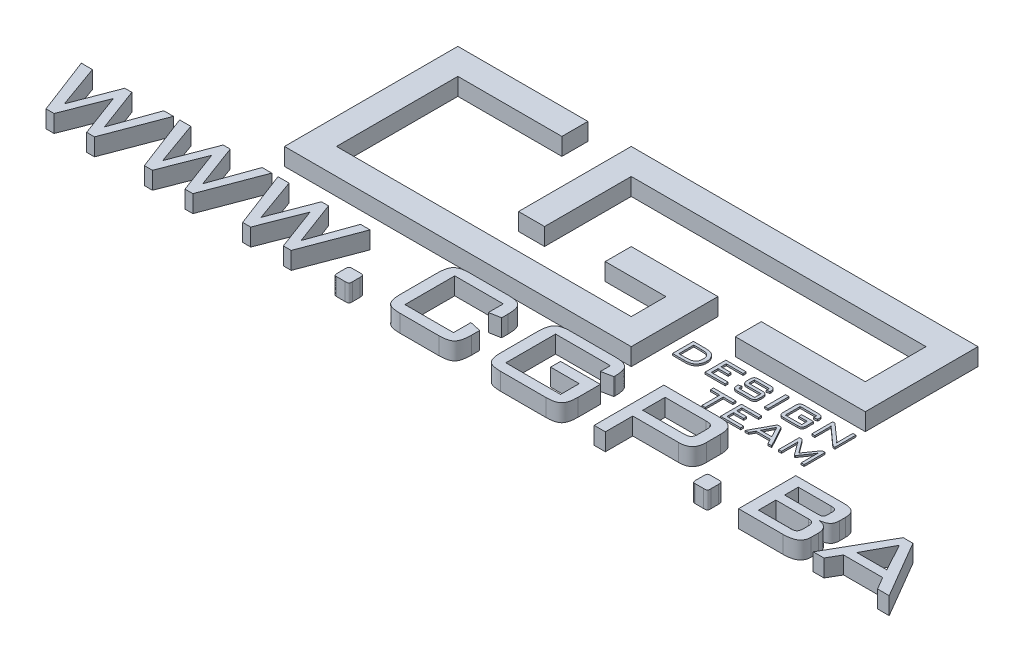
SolidWorks part; units mm, degrees
ref_plane "Front Plane" through (0, 0, 0) normal (0, 0, 1) x (1, 0, 0)
ref_plane "Top Plane" through (0, 0, 0) normal (0, 1, 0) x (1, 0, 0)
ref_plane "Right Plane" through (0, 0, 0) normal (1, 0, 0) x (0, 0, -1)
sketch "Sketch1" plane through (0, 0, 0) normal (0, 0, 1) x (1, 0, 0)
  line L0 (-150, 0) -> (50, 0)
  line L1 (50, 0) -> (50, 50)
  line L2 (50, 50) -> (0, 50)
  line L3 (-150, 0) -> (-150, 100)
  line L4 (-150, 100) -> (-75, 100)
  line L5 (-50, 100) -> (150, 100)
  line L6 (150, 100) -> (150, 35)
  line L7 (150, 35) -> (75, 35)
  line L8 (35, 35) -> (0, 35)
  line L9 (35, 15) -> (35, 35)
  line L10 (-135, 15) -> (35, 15)
  line L11 (-135, 15) -> (-135, 85)
  line L12 (-135, 85) -> (-75, 85)
  line L13 (-50, 100) -> (-50, 35)
  line L14 (135, 50) -> (75, 50)
  line L15 (135, 85) -> (135, 50)
  line L16 (-35, 85) -> (135, 85)
  line L17 (-35, 85) -> (-35, 35)
  line L18 (-35, 35) -> (-50, 35)
  line L19 (-75, 100) -> (-75, 85)
  line L20 (0, 50) -> (0, 35)
  line L21 (75, 50) -> (75, 35)
  dimension "D1" = 200
  dimension "D2" = 50
  dimension "D3" = 50
  dimension "D4" = 100
  dimension "D5" = 75
  dimension "D6" = 200
  dimension "D8" = 25
  dimension "D9" = 75
  dimension "D10" = 15
  dimension "D11" = 15
sketch "Sketch4" plane through (0, 0, 0) normal (0, 1, 0) x (1, 0, 0)
  line L0 (-150, -35) -> (50, -35)
  line L1 (50, -35) -> (50, 15)
  line L2 (50, 15) -> (0, 15)
  line L3 (-150, -35) -> (-150, 65)
  line L4 (-150, 65) -> (-75, 65)
  line L5 (-50, 65) -> (150, 65)
  line L6 (150, 65) -> (150, 0)
  line L7 (150, 0) -> (75, 0)
  line L8 (35, 0) -> (0, 0)
  line L9 (35, -20) -> (35, 0)
  line L10 (-135, -20) -> (35, -20)
  line L11 (-135, -20) -> (-135, 50)
  line L12 (-135, 50) -> (-75, 50)
  line L13 (-50, 65) -> (-50, 0)
  line L14 (135, 15) -> (75, 15)
  line L15 (135, 50) -> (135, 15)
  line L16 (-35, 50) -> (135, 50)
  line L17 (-35, 50) -> (-35, 0)
  line L18 (-35, 0) -> (-50, 0)
  line L19 (-75, 65) -> (-75, 50)
  line L20 (0, 15) -> (0, 0)
  line L21 (75, 15) -> (75, 0)
  dimension "D1" = 200
  dimension "D2" = 50
  dimension "D3" = 50
  dimension "D4" = 100
  dimension "D5" = 75
  dimension "D6" = 200
  dimension "D7" = 25
  dimension "D8" = 75
  dimension "D9" = 15
  dimension "D10" = 50
  dimension "D11" = 70
  dimension "D12" = 60
  dimension "D13" = 170
  dimension "D14" = 35
  dimension "D15" = 20
  dimension "D16" = 170
  dimension "D17" = 15
extrude "Boss-Extrude2" add sketch "Sketch4" along normal blind 10
sketch "Sketch6" plane through (0, 0, 0) normal (0, 1, 0) x (1, 0, 0)
  line L0 (50, -17.5) -> (153, -17.5) construction
  line L1 (-150, -35) -> (50, -35) construction
  line L2 (50, -35) -> (153, -35) construction
  line L3 (50, -35) -> (50, 15) construction
  text T0 "DESIGN" font "BankGothic Lt BT" height in points 45
  text T1 "TEAM" font "BankGothic Lt BT" height in points 45
  dimension "D1" = 103
  dimension "D2" = 103
  dimension "D3" = 17.5
extrude "Boss-Extrude4" add sketch "Sketch6" along normal blind 1 separate body
sketch "Sketch7" plane through (0, 0, 0) normal (0, 1, 0) x (1, 0, 0)
  line L0 (-150, -61.1733) -> (50, -61.1733) construction
  line L1 (-83.6915, -73.2799) -> (8.5878, -73.2799) construction
  line L2 (-83.6915, -82.2799) -> (8.5878, -82.2799) construction
  line L3 (-83.6915, -91.2799) -> (8.5878, -91.2799) construction
  line L4 (-83.6915, -100.2799) -> (8.5878, -100.2799) construction
  line L5 (-83.6915, -109.2799) -> (8.5878, -109.2799) construction
  line L6 (-83.6915, -118.2799) -> (8.5878, -118.2799) construction
  text T0 "Engineering-Design-Architecture-IT \r\nEducation:" font "BankGothic Lt BT" height in points 20
  text T1 "Solidworks\r\n" font "BankGothic Lt BT" height in points 21
  text T2 "AutoCAD" font "BankGothic Lt BT" height in points 21
  text T3 "CATIA V5" font "BankGothic Lt BT" height in points 21
  text T4 "3D Printing" font "BankGothic Lt BT" height in points 21
  text T5 "3ds MAX" font "BankGothic Lt BT" height in points 21
  text T6 "Maya 3D" font "BankGothic Lt BT" height in points 21
  dimension "D1" = 9
  dimension "D2" = 9
  dimension "D3" = 9
  dimension "D4" = 9
  dimension "D5" = 9
extrude "Boss-Extrude5" [suppressed] add sketch "Sketch7" along normal blind 1 separate body
sketch "Sketch9" plane through (0, 0, 0) normal (0, 1, 0) x (1, 0, 0)
  line L0 (-350, -85) -> (350, -85) construction
  line L1 (-150, -35) -> (50, -35) construction
  text T0 "www.CGP.ba" font "BankGothic Lt BT" height in points 150
  dimension "D1" = 700
  dimension "D2" = 350
  dimension "D3" = 50
extrude "Boss-Extrude6" add sketch "Sketch9" along normal up to surface (10 mm away) separate body up to face at (-45.8333, 10, -12.5)
sketch "Sketch8" plane through (0, 0, 0) normal (0, 1, 0) x (1, 0, 0)
  line L0 (-50, 65) -> (-50, 0) construction
  line L1 (-50, 0) -> (-35, 0) construction
  line L2 (-35, 0) -> (-35, 50) construction
  line L3 (-35, 50) -> (135, 50) construction
  line L4 (135, 50) -> (135, 15) construction
  line L5 (135, 15) -> (75, 15) construction
  line L6 (75, 15) -> (75, 0) construction
  line L7 (75, 0) -> (150, 0) construction
  line L8 (150, 0) -> (150, 65) construction
  line L9 (150, 65) -> (-50, 65) construction
  line L10 (-150, 65) -> (-150, -35) construction
  line L11 (-150, -35) -> (50, -35) construction
  line L12 (50, -35) -> (50, 15) construction
  line L13 (50, 15) -> (0, 15) construction
  line L14 (0, 15) -> (0, 0) construction
  line L15 (0, 0) -> (35, 0) construction
  line L16 (35, 0) -> (35, -20) construction
  line L17 (35, -20) -> (-135, -20) construction
  line L18 (-135, -20) -> (-135, 50) construction
  line L19 (-135, 50) -> (-75, 50) construction
  line L20 (-75, 50) -> (-75, 65) construction
  line L21 (-75, 65) -> (-150, 65) construction
  line L22 (-50, 65) -> (-50, 0)
  line L23 (-50, 0) -> (-35, 0)
  line L24 (-35, 0) -> (-35, 50)
  line L25 (-35, 50) -> (135, 50)
  line L26 (135, 50) -> (135, 15)
  line L27 (135, 15) -> (75, 15)
  line L28 (75, 15) -> (75, 0)
  line L29 (75, 0) -> (150, 0)
  line L30 (150, 0) -> (150, 65)
  line L31 (150, 65) -> (-50, 65)
  line L32 (-150, 65) -> (-150, -35)
  line L33 (-150, -35) -> (50, -35)
  line L34 (50, -35) -> (50, 15)
  line L35 (50, 15) -> (0, 15)
  line L36 (0, 15) -> (0, 0)
  line L37 (0, 0) -> (35, 0)
  line L38 (35, 0) -> (35, -20)
  line L39 (35, -20) -> (-135, -20)
  line L40 (-135, -20) -> (-135, 50)
  line L41 (-135, 50) -> (-75, 50)
  line L42 (-75, 50) -> (-75, 65)
  line L43 (-75, 65) -> (-150, 65)
  line L44 (115.7393, -35) -> (117.7046, -35) construction
  line L45 (117.7046, -35) -> (119.2325, -32.2001) construction
  line L46 (119.2325, -32.2001) -> (127.3126, -32.2001) construction
  line L47 (127.3126, -32.2001) -> (128.8371, -35) construction
  line L48 (128.8371, -35) -> (131.0312, -35) construction
  line L49 (131.0312, -35) -> (124.3982, -22.9387) construction
  line L50 (124.3982, -22.9387) -> (122.2612, -22.9387) construction
  line L51 (122.2612, -22.9387) -> (115.7393, -35) construction
  line L52 (137.3614, -26.58) -> (142.2175, -33.1053) construction
  line L53 (142.2175, -33.1053) -> (142.7392, -33.1053) construction
  line L54 (142.7392, -33.1053) -> (147.4102, -26.3949) construction
  line L55 (148.0463, -26.8627) -> (148.0463, -35) construction
  line L56 (148.0463, -35) -> (149.7693, -35) construction
  line L57 (149.7693, -35) -> (149.7693, -22.9387) construction
  line L58 (149.7693, -22.9387) -> (148.0463, -22.9387) construction
  line L59 (148.0463, -22.9387) -> (142.507, -30.79) construction
  line L60 (142.507, -30.79) -> (136.5705, -22.9387) construction
  line L61 (136.5705, -22.9387) -> (134.9081, -22.9387) construction
  line L62 (134.9081, -22.9387) -> (134.9081, -35) construction
  line L63 (134.9081, -35) -> (136.6311, -35) construction
  line L64 (136.6311, -35) -> (136.6311, -26.8627) construction
  line L65 (136.6311, -17.5) -> (138.3542, -17.5) construction
  line L66 (138.3542, -17.5) -> (138.3542, -10.3925) construction
  line L67 (139.4681, -9.1136) -> (148.8405, -17.5) construction
  line L68 (148.8405, -17.5) -> (149.9847, -17.5) construction
  line L69 (149.9847, -17.5) -> (149.9847, -5.4387) construction
  line L70 (149.9847, -5.4387) -> (148.2616, -5.4387) construction
  line L71 (148.2616, -5.4387) -> (148.2616, -12.0583) construction
  line L72 (147.04, -13.5054) -> (137.9133, -5.4387) construction
  line L73 (137.9133, -5.4387) -> (136.6311, -5.4387) construction
  line L74 (136.6311, -5.4387) -> (136.6311, -17.5) construction
  line L75 (92.6936, -24.6618) -> (98.2935, -24.6618) construction
  line L76 (98.2935, -24.6618) -> (98.2935, -22.9387) construction
  line L77 (98.2935, -22.9387) -> (85.3707, -22.9387) construction
  line L78 (85.3707, -22.9387) -> (85.3707, -24.6618) construction
  line L79 (85.3707, -24.6618) -> (90.7552, -24.6618) construction
  line L80 (90.7552, -24.6618) -> (90.7552, -35) construction
  line L81 (90.7552, -35) -> (92.6936, -35) construction
  line L82 (92.6936, -35) -> (92.6936, -24.6618) construction
  line L83 (101.5242, -35) -> (113.1547, -35) construction
  line L84 (113.1547, -35) -> (113.1547, -33.277) construction
  line L85 (113.1547, -33.277) -> (103.4626, -33.277) construction
  line L86 (103.4626, -33.277) -> (103.4626, -29.4001) construction
  line L87 (103.4626, -29.4001) -> (109.2779, -29.4001) construction
  line L88 (109.2779, -29.4001) -> (109.2779, -27.6771) construction
  line L89 (109.2779, -27.6771) -> (103.4626, -27.6771) construction
  line L90 (103.4626, -27.6771) -> (103.4626, -24.6618) construction
  line L91 (103.4626, -24.6618) -> (113.1547, -24.6618) construction
  line L92 (113.1547, -24.6618) -> (113.1547, -22.9387) construction
  line L93 (113.1547, -22.9387) -> (101.5242, -22.9387) construction
  line L94 (101.5242, -22.9387) -> (101.5242, -35) construction
  line L95 (129.0928, -7.1618) -> (129.0928, -8.8848) construction
  line L96 (129.0928, -8.8848) -> (131.0312, -8.4944) construction
  line L97 (131.0312, -8.4944) -> (131.0312, -8.205) construction
  line L98 (128.2582, -5.4387) -> (120.4305, -5.4387) construction
  line L99 (117.6777, -8.3396) -> (117.6777, -14.7034) construction
  line L100 (120.4305, -17.5) -> (128.2582, -17.5) construction
  line L101 (131.0312, -14.7034) -> (131.0312, -10.8232) construction
  line L102 (131.0312, -10.8232) -> (124.1391, -10.8232) construction
  line L103 (124.1391, -10.8232) -> (124.1391, -12.5463) construction
  line L104 (124.1391, -12.5463) -> (129.0928, -12.5463) construction
  line L105 (129.0928, -12.5463) -> (129.0928, -15.777) construction
  line L106 (129.0928, -15.777) -> (119.6161, -15.777) construction
  line L107 (119.6161, -15.777) -> (119.6161, -7.1618) construction
  line L108 (119.6161, -7.1618) -> (129.0928, -7.1618) construction
  line L109 (109.4932, -17.5) -> (111.4317, -17.5) construction
  line L110 (111.4317, -17.5) -> (111.4317, -5.4387) construction
  line L111 (111.4317, -5.4387) -> (109.4932, -5.4387) construction
  line L112 (109.4932, -5.4387) -> (109.4932, -17.5) construction
  line L113 (101.7396, -7.1618) -> (101.7396, -8.8848) construction
  line L114 (101.7396, -8.8848) -> (103.4626, -8.4002) construction
  line L115 (103.4626, -8.4002) -> (103.4626, -8.1512) construction
  line L116 (100.6223, -5.4387) -> (94.1373, -5.4387) construction
  line L117 (91.4013, -8.3564) -> (91.4013, -9.3627) construction
  line L118 (94.1373, -12.1155) -> (101.9549, -12.1155) construction
  line L119 (101.9549, -12.1155) -> (101.9549, -15.777) construction
  line L120 (101.9549, -15.777) -> (92.6936, -15.777) construction
  line L121 (92.6936, -15.777) -> (92.6936, -13.8385) construction
  line L122 (92.6936, -13.8385) -> (90.9706, -14.2727) construction
  line L123 (90.9706, -14.2727) -> (90.9706, -14.6025) construction
  line L124 (93.6897, -17.5) -> (100.7939, -17.5) construction
  line L125 (103.678, -14.6025) -> (103.678, -13.2328) construction
  line L126 (100.7939, -10.3925) -> (93.1244, -10.3925) construction
  line L127 (93.1244, -10.3925) -> (93.1244, -7.1618) construction
  line L128 (93.1244, -7.1618) -> (101.7396, -7.1618) construction
  line L129 (75.0324, -17.5) -> (86.663, -17.5) construction
  line L130 (86.663, -17.5) -> (86.663, -15.777) construction
  line L131 (86.663, -15.777) -> (76.9709, -15.777) construction
  line L132 (76.9709, -15.777) -> (76.9709, -11.9001) construction
  line L133 (76.9709, -11.9001) -> (82.7861, -11.9001) construction
  line L134 (82.7861, -11.9001) -> (82.7861, -10.1771) construction
  line L135 (82.7861, -10.1771) -> (76.9709, -10.1771) construction
  line L136 (76.9709, -10.1771) -> (76.9709, -7.1618) construction
  line L137 (76.9709, -7.1618) -> (86.663, -7.1618) construction
  line L138 (86.663, -7.1618) -> (86.663, -5.4387) construction
  line L139 (86.663, -5.4387) -> (75.0324, -5.4387) construction
  line L140 (75.0324, -5.4387) -> (75.0324, -17.5) construction
  line L141 (62.8567, -5.4387) -> (56.2944, -5.4387) construction
  line L142 (56.2944, -5.4387) -> (56.2944, -17.5) construction
  line L143 (56.2944, -17.5) -> (62.8567, -17.5) construction
  line L144 (115.7393, -35) -> (117.7046, -35)
  line L145 (117.7046, -35) -> (119.2325, -32.2001)
  line L146 (119.2325, -32.2001) -> (127.3126, -32.2001)
  line L147 (127.3126, -32.2001) -> (128.8371, -35)
  line L148 (128.8371, -35) -> (131.0312, -35)
  line L149 (131.0312, -35) -> (124.3982, -22.9387)
  line L150 (124.3982, -22.9387) -> (122.2612, -22.9387)
  line L151 (122.2612, -22.9387) -> (115.7393, -35)
  line L152 (137.3614, -26.58) -> (142.2175, -33.1053)
  line L153 (142.2175, -33.1053) -> (142.7392, -33.1053)
  line L154 (142.7392, -33.1053) -> (147.4102, -26.3949)
  line L155 (148.0463, -26.8627) -> (148.0463, -35)
  line L156 (148.0463, -35) -> (149.7693, -35)
  line L157 (149.7693, -35) -> (149.7693, -22.9387)
  line L158 (149.7693, -22.9387) -> (148.0463, -22.9387)
  line L159 (148.0463, -22.9387) -> (142.507, -30.79)
  line L160 (142.507, -30.79) -> (136.5705, -22.9387)
  line L161 (136.5705, -22.9387) -> (134.9081, -22.9387)
  line L162 (134.9081, -22.9387) -> (134.9081, -35)
  line L163 (134.9081, -35) -> (136.6311, -35)
  line L164 (136.6311, -35) -> (136.6311, -26.8627)
  line L165 (136.6311, -17.5) -> (138.3542, -17.5)
  line L166 (138.3542, -17.5) -> (138.3542, -10.3925)
  line L167 (139.4681, -9.1136) -> (148.8405, -17.5)
  line L168 (148.8405, -17.5) -> (149.9847, -17.5)
  line L169 (149.9847, -17.5) -> (149.9847, -5.4387)
  line L170 (149.9847, -5.4387) -> (148.2616, -5.4387)
  line L171 (148.2616, -5.4387) -> (148.2616, -12.0583)
  line L172 (147.04, -13.5054) -> (137.9133, -5.4387)
  line L173 (137.9133, -5.4387) -> (136.6311, -5.4387)
  line L174 (136.6311, -5.4387) -> (136.6311, -17.5)
  line L175 (92.6936, -24.6618) -> (98.2935, -24.6618)
  line L176 (98.2935, -24.6618) -> (98.2935, -22.9387)
  line L177 (98.2935, -22.9387) -> (85.3707, -22.9387)
  line L178 (85.3707, -22.9387) -> (85.3707, -24.6618)
  line L179 (85.3707, -24.6618) -> (90.7552, -24.6618)
  line L180 (90.7552, -24.6618) -> (90.7552, -35)
  line L181 (90.7552, -35) -> (92.6936, -35)
  line L182 (92.6936, -35) -> (92.6936, -24.6618)
  line L183 (101.5242, -35) -> (113.1547, -35)
  line L184 (113.1547, -35) -> (113.1547, -33.277)
  line L185 (113.1547, -33.277) -> (103.4626, -33.277)
  line L186 (103.4626, -33.277) -> (103.4626, -29.4001)
  line L187 (103.4626, -29.4001) -> (109.2779, -29.4001)
  line L188 (109.2779, -29.4001) -> (109.2779, -27.6771)
  line L189 (109.2779, -27.6771) -> (103.4626, -27.6771)
  line L190 (103.4626, -27.6771) -> (103.4626, -24.6618)
  line L191 (103.4626, -24.6618) -> (113.1547, -24.6618)
  line L192 (113.1547, -24.6618) -> (113.1547, -22.9387)
  line L193 (113.1547, -22.9387) -> (101.5242, -22.9387)
  line L194 (101.5242, -22.9387) -> (101.5242, -35)
  line L195 (129.0928, -7.1618) -> (129.0928, -8.8848)
  line L196 (129.0928, -8.8848) -> (131.0312, -8.4944)
  line L197 (131.0312, -8.4944) -> (131.0312, -8.205)
  line L198 (128.2582, -5.4387) -> (120.4305, -5.4387)
  line L199 (117.6777, -8.3396) -> (117.6777, -14.7034)
  line L200 (120.4305, -17.5) -> (128.2582, -17.5)
  line L201 (131.0312, -14.7034) -> (131.0312, -10.8232)
  line L202 (131.0312, -10.8232) -> (124.1391, -10.8232)
  line L203 (124.1391, -10.8232) -> (124.1391, -12.5463)
  line L204 (124.1391, -12.5463) -> (129.0928, -12.5463)
  line L205 (129.0928, -12.5463) -> (129.0928, -15.777)
  line L206 (129.0928, -15.777) -> (119.6161, -15.777)
  line L207 (119.6161, -15.777) -> (119.6161, -7.1618)
  line L208 (119.6161, -7.1618) -> (129.0928, -7.1618)
  line L209 (109.4932, -17.5) -> (111.4317, -17.5)
  line L210 (111.4317, -17.5) -> (111.4317, -5.4387)
  line L211 (111.4317, -5.4387) -> (109.4932, -5.4387)
  line L212 (109.4932, -5.4387) -> (109.4932, -17.5)
  line L213 (101.7396, -7.1618) -> (101.7396, -8.8848)
  line L214 (101.7396, -8.8848) -> (103.4626, -8.4002)
  line L215 (103.4626, -8.4002) -> (103.4626, -8.1512)
  line L216 (100.6223, -5.4387) -> (94.1373, -5.4387)
  line L217 (91.4013, -8.3564) -> (91.4013, -9.3627)
  line L218 (94.1373, -12.1155) -> (101.9549, -12.1155)
  line L219 (101.9549, -12.1155) -> (101.9549, -15.777)
  line L220 (101.9549, -15.777) -> (92.6936, -15.777)
  line L221 (92.6936, -15.777) -> (92.6936, -13.8385)
  line L222 (92.6936, -13.8385) -> (90.9706, -14.2727)
  line L223 (90.9706, -14.2727) -> (90.9706, -14.6025)
  line L224 (93.6897, -17.5) -> (100.7939, -17.5)
  line L225 (103.678, -14.6025) -> (103.678, -13.2328)
  line L226 (100.7939, -10.3925) -> (93.1244, -10.3925)
  line L227 (93.1244, -10.3925) -> (93.1244, -7.1618)
  line L228 (93.1244, -7.1618) -> (101.7396, -7.1618)
  line L229 (75.0324, -17.5) -> (86.663, -17.5)
  line L230 (86.663, -17.5) -> (86.663, -15.777)
  line L231 (86.663, -15.777) -> (76.9709, -15.777)
  line L232 (76.9709, -15.777) -> (76.9709, -11.9001)
  line L233 (76.9709, -11.9001) -> (82.7861, -11.9001)
  line L234 (82.7861, -11.9001) -> (82.7861, -10.1771)
  line L235 (82.7861, -10.1771) -> (76.9709, -10.1771)
  line L236 (76.9709, -10.1771) -> (76.9709, -7.1618)
  line L237 (76.9709, -7.1618) -> (86.663, -7.1618)
  line L238 (86.663, -7.1618) -> (86.663, -5.4387)
  line L239 (86.663, -5.4387) -> (75.0324, -5.4387)
  line L240 (75.0324, -5.4387) -> (75.0324, -17.5)
  line L241 (62.8567, -5.4387) -> (56.2944, -5.4387)
  line L242 (56.2944, -5.4387) -> (56.2944, -17.5)
  line L243 (56.2944, -17.5) -> (62.8567, -17.5)
  line L244 (120.0671, -30.477) -> (126.4982, -30.477) construction
  line L245 (62.5707, -7.1618) -> (58.2328, -7.1618) construction
  line L246 (58.2328, -15.777) -> (62.5707, -15.777) construction
  line L247 (58.2328, -7.1618) -> (58.2328, -15.777) construction
  line L248 (123.2776, -24.3151) -> (120.0671, -30.477) construction
  line L249 (126.4982, -30.477) -> (123.2776, -24.3151) construction
  line L250 (120.0671, -30.477) -> (126.4982, -30.477)
  line L251 (126.4982, -30.477) -> (123.2776, -24.3151)
  line L252 (123.2776, -24.3151) -> (120.0671, -30.477)
  line L253 (58.2328, -7.1618) -> (58.2328, -15.777)
  line L254 (58.2328, -15.777) -> (62.5707, -15.777)
  line L255 (62.5707, -7.1618) -> (58.2328, -7.1618)
  line L256 (-350, -85) -> (350, -85) construction
  spline S0 degree 3 poles (-11857.5173, -5035.0417) (223.8845, 44.5646) (129.8104, -11.8679) (136.8463, -25.7989) (146.9319, -42.5935) (241.0333, -3.6078) (-10668.9913, -7250.1358) knots -28.406317 -28.406317 -28.406317 -28.406317 0.231846 0.47301 0.729943 36.845841 36.845841 36.845841 36.845841 only from (136.5403, -25.0959) to (137.3042, -26.4992) construction
  spline S1 degree 3 poles (-10429.0902, -7596.536) (174.5683, 13.3543) (101.8761, -50.7131) (170.2646, -13.4441) (-10412.5762, -7620.2349) knots -161.421544 -161.421544 -161.421544 -161.421544 0.660055 130.391888 130.391888 130.391888 130.391888 only from (137.3042, -26.4992) to (137.3614, -26.58) construction
  spline S2 degree 3 poles (11167.6876, -6918.2798) (60.9845, -5.6512) (140.7273, -38.4158) (147.7359, -25.8618) (159.6741, -3.8807) (94.5984, 58.2585) (11700.1863, -5984.1183) knots -28.317786 -28.317786 -28.317786 -28.317786 0.181459 0.403568 0.676028 50.663628 50.663628 50.663628 50.663628 only from (147.4102, -26.3949) to (148.1304, -25.0959) construction
  spline S3 degree 3 poles (13138.3063, -493.3359) (110.4857, 16.7249) (149.0894, -5.1548) (148.113, -25.511) (148.0995, -25.7723) (148.0841, -26.0573) (148.0663, -26.332) (148.0574, -26.562) (147.427, -40.9271) (181.1051, -56.4481) (-12842.8844, 397.5272) knots -34.188276 -34.188276 -34.188276 -34.188276 0.102808 0.226604 0.375198 0.54669 0.710585 0.841984 0.937187 25.097075 25.097075 25.097075 25.097075 only from (148.1304, -25.0959) to (148.0463, -26.8627) construction
  spline S4 degree 3 poles (13134.2488, 92.1401) (64.9255, -64.4576) (137.2485, -44.9293) (136.6241, -26.2973) (136.6193, -26.056) (136.6049, -25.7789) (135.392, -6.6179) (49.1848, 4.3568) (13070.3412, 1266.8473) knots -31.124298 -31.124298 -31.124298 -31.124298 0.171077 0.325093 0.462008 0.579999 0.795333 32.983236 32.983236 32.983236 32.983236 only from (136.6311, -26.8627) to (136.5403, -25.0959) construction
  spline S5 degree 3 poles (-12852.9859, -423.6431) (191.749, -75.9099) (138.2826, -43.4642) (138.3508, -9.6127) (138.3337, -9.2595) (138.3177, -8.8319) (136.828, 17.829) (38.8658, 35.8731) (13079.0307, 1212.2845) knots -37.984262 -37.984262 -37.984262 -37.984262 0.154074 0.299236 0.431757 0.555372 0.784993 30.727959 30.727959 30.727959 30.727959 only from (138.3542, -10.3925) to (138.2263, -7.7541) construction
  spline S6 degree 3 poles (-10392.0012, -7627.7634) (205.8181, 76.9117) (129.1874, 3.0002) (138.6593, -8.3375) (151.5049, -22.2582) (240.2493, 40.6491) (-8966.6579, -9284.0682) knots -27.433658 -27.433658 -27.433658 -27.433658 0.217327 0.454722 0.715257 36.343824 36.343824 36.343824 36.343824 only from (138.2263, -7.7541) to (139.2594, -8.9319) construction
  spline S7 degree 3 poles (-8404.7278, -9804.8374) (159.3618, 51.0936) (104.2128, -47.5494) (186.1544, 11.8744) (-8352.3439, -9849.6052) knots -131.172965 -131.172965 -131.172965 -131.172965 0.585786 117.859888 117.859888 117.859888 117.859888 only from (139.2594, -8.9319) to (139.4681, -9.1136) construction
  spline S8 degree 3 poles (-12848.8833, 35.3356) (195.9643, 83.1185) (147.6844, 34.9312) (148.27, -13.0343) (148.2824, -13.4417) (148.3099, -13.8996) (150.7071, -42.4425) (247.7099, -60.1642) (-12756.4188, -1560.0892) knots -47.938009 -47.938009 -47.938009 -47.938009 0.177743 0.335121 0.47218 0.588984 0.798076 29.369031 29.369031 29.369031 29.369031 only from (148.2616, -12.0583) to (148.4333, -15.0231) construction
  spline S9 degree 3 poles (10107.9253, 8337.0355) (109.546, -117.3861) (165.7358, -34.3868) (147.7182, -14.1784) (133.927, 0.5871) (49.8222, -56.5392) (9209.6841, 9303.553) knots -38.587878 -38.587878 -38.587878 -38.587878 0.280566 0.544106 0.785299 29.647382 29.647382 29.647382 29.647382 only from (148.4333, -15.0231) to (147.04, -13.5054) construction
  spline S10 degree 3 poles (13124.7102, 322.0599) (46.3147, -48.8822) (132.4283, -26.9336) (130.9995, -7.4902) (130.9518, -7.1734) (130.8902, -6.8854) (130.8054, -6.6289) (130.7059, -6.4003) (130.5838, -6.2038) (130.4432, -6.0325) (130.2743, -5.8906) (130.0786, -5.7654) (129.8478, -5.6699) (129.5911, -5.5779) (129.3008, -5.5191) (128.981, -5.4698) (108.9247, -4.0637) (87.1226, -88.268) (350.261, 12990.6827) knots -12.437155 -12.437155 -12.437155 -12.437155 0.081715 0.157063 0.226376 0.2899 0.348251 0.401791 0.451579 0.498176 0.545245 0.594415 0.648622 0.707205 0.77144 0.840754 0.917556 13.828194 13.828194 13.828194 13.828194 only from (131.0312, -8.205) to (128.2582, -5.4387) construction
  spline S11 degree 3 poles (-105.7363, 12991.0679) (162.3538, -88.1424) (140.1387, -4.0741) (119.6997, -5.4694) (119.3784, -5.5213) (119.0891, -5.5873) (118.829, -5.6695) (118.6038, -5.7779) (118.4076, -5.9015) (118.2459, -6.0514) (118.1053, -6.2242) (117.9952, -6.4334) (117.8904, -6.6688) (117.8179, -6.9421) (117.752, -7.2436) (117.7107, -7.5804) (116.2374, -27.6165) (205.0589, -51.332) (-12871.2788, 477.8805) knots -12.757928 -12.757928 -12.757928 -12.757928 0.081869 0.156811 0.225256 0.288093 0.34503 0.397871 0.446233 0.491568 0.537136 0.586836 0.641035 0.700274 0.765736 0.836795 0.915285 13.506697 13.506697 13.506697 13.506697 only from (120.4305, -5.4387) to (117.6777, -8.3396) construction
  spline S12 degree 3 poles (-12870.2127, -536.7062) (205.6031, 26.9879) (116.2302, 3.8053) (117.7109, -15.4369) (117.7516, -15.7615) (117.8181, -16.0517) (117.8912, -16.3146) (117.9938, -16.5422) (118.1076, -16.7424) (118.2446, -16.9114) (118.4092, -17.0535) (118.6029, -17.1754) (118.8309, -17.274) (119.0884, -17.3595) (119.3787, -17.4204) (119.7, -17.4685) (139.6497, -18.8943) (161.8948, 67.2885) (-177.1063, -13012.1266) knots -12.239686 -12.239686 -12.239686 -12.239686 0.083416 0.160496 0.230741 0.294604 0.352875 0.406768 0.455517 0.501383 0.546608 0.595492 0.648722 0.706735 0.770598 0.840227 0.916584 13.686467 13.686467 13.686467 13.686467 only from (117.6777, -14.7034) to (120.4305, -17.5) construction
  spline S13 degree 3 poles (691.8805, -13003.5259) (86.7987, 71.8095) (110.041, -18.9646) (128.9893, -17.4663) (129.3133, -17.4269) (129.6024, -17.3569) (129.8622, -17.279) (130.0885, -17.1769) (130.287, -17.0608) (130.454, -16.9181) (130.5942, -16.7493) (130.7125, -16.5515) (130.8094, -16.3208) (130.8932, -16.0599) (130.9562, -15.7656) (130.9983, -15.4403) (132.4721, 4.0008) (43.2185, 26.8544) (13121.3064, -461.4597) knots -12.007928 -12.007928 -12.007928 -12.007928 0.083102 0.159172 0.229154 0.292937 0.35051 0.40354 0.452476 0.498078 0.544231 0.593167 0.645906 0.705075 0.769404 0.839385 0.916176 13.317245 13.317245 13.317245 13.317245 only from (128.2582, -17.5) to (131.0312, -14.7034) construction
  spline S14 degree 3 poles (13100.7829, 117.6058) (21.7117, -47.3846) (104.8162, -26.8799) (103.4321, -7.4617) (103.3781, -7.1559) (103.3195, -6.8745) (103.2291, -6.6244) (103.1272, -6.4) (103.001, -6.2052) (102.8539, -6.0372) (102.6814, -5.8912) (102.4768, -5.7728) (102.2457, -5.6659) (101.9804, -5.5842) (101.6847, -5.5169) (101.3571, -5.471) (81.5886, -4.028) (58.7445, -90.9997) (510.3395, 12986.6348) knots -12.422456 -12.422456 -12.422456 -12.422456 0.07882 0.151279 0.218562 0.28068 0.3379 0.391096 0.440672 0.488232 0.53587 0.586916 0.641436 0.701191 0.767027 0.838525 0.916075 13.64938 13.64938 13.64938 13.64938 only from (103.4626, -8.1512) to (100.6223, -5.4387) construction
  spline S15 degree 3 poles (-7.2526, 12991.9876) (135.6682, -86.521) (114.0695, -4.092) (93.4098, -5.469) (93.0903, -5.5224) (92.8003, -5.5822) (92.5449, -5.6707) (92.319, -5.7744) (92.125, -5.8987) (91.9611, -6.0469) (91.8286, -6.2248) (91.7121, -6.4301) (91.6174, -6.6698) (91.535, -6.9417) (91.4773, -7.2488) (91.4342, -7.5882) (89.9626, -27.8645) (179.2689, -51.165) (-12901.1143, 380.9641) knots -12.878062 -12.878062 -12.878062 -12.878062 0.081062 0.155914 0.224278 0.286189 0.343285 0.395117 0.443421 0.488702 0.534339 0.583359 0.637875 0.697245 0.763183 0.835568 0.913964 13.636634 13.636634 13.636634 13.636634 only from (94.1373, -5.4387) to (91.4013, -8.3564) construction
  spline S16 degree 3 poles (-12899.2302, -456.4362) (179.1846, 31.5457) (89.9618, 9.0253) (91.4343, -10.0872) (91.4768, -10.4067) (91.5367, -10.6964) (91.6155, -10.9538) (91.7138, -11.1798) (91.8285, -11.3736) (91.9615, -11.5415) (92.1265, -11.6792) (92.3202, -11.796) (92.5444, -11.8983) (92.8018, -11.9762) (93.0895, -12.0413) (93.4106, -12.0824) (112.5294, -13.5594) (135.4313, 75.6066) (-406.8738, -13000.356) knots -12.278731 -12.278731 -12.278731 -12.278731 0.083533 0.159937 0.230172 0.293814 0.352892 0.405697 0.454313 0.499615 0.544822 0.593817 0.646921 0.7053 0.769098 0.839333 0.916467 13.284831 13.284831 13.284831 13.284831 only from (91.4013, -9.3627) to (94.1373, -12.1155) construction
  spline S17 degree 3 poles (-12900.5854, -432.3179) (178.3933, 28.2475) (89.5343, 4.8377) (91.0034, -15.3662) (91.0458, -15.7025) (91.106, -16.0066) (91.185, -16.2775) (91.2827, -16.5158) (91.3964, -16.7214) (91.5341, -16.8943) (91.6985, -17.0401) (91.8915, -17.1644) (92.1166, -17.2676) (92.37, -17.3554) (92.6553, -17.4219) (92.9716, -17.4678) (112.2697, -18.9136) (134.5694, 68.6328) (-303.0775, -13008.9874) knots -12.688933 -12.688933 -12.688933 -12.688933 0.085972 0.164964 0.237187 0.302221 0.362727 0.416994 0.466386 0.512246 0.55739 0.606061 0.658286 0.715138 0.776981 0.845048 0.91904 13.123251 13.123251 13.123251 13.123251 only from (90.9706, -14.6025) to (93.6897, -17.5) construction
  spline S18 degree 3 poles (473.6813, -13010.1915) (57.5199, 68.2049) (80.9603, -18.9099) (101.5579, -17.4679) (101.8955, -17.422) (102.1982, -17.3552) (102.4683, -17.2716) (102.7038, -17.1687) (102.907, -17.0461) (103.0804, -16.9024) (103.2251, -16.7286) (103.3456, -16.523) (103.4505, -16.2861) (103.5324, -16.0144) (103.6005, -15.7098) (103.6456, -15.3709) (105.1002, 5.141) (16.8712, 28.7704) (13095.5271, -422.2015) knots -12.557619 -12.557619 -12.557619 -12.557619 0.083448 0.160121 0.230317 0.29441 0.352014 0.405236 0.453284 0.498679 0.544074 0.592718 0.645939 0.704206 0.768299 0.839184 0.915857 13.505023 13.505023 13.505023 13.505023 only from (100.7939, -17.5) to (103.678, -14.6025) construction
  spline S19 degree 3 poles (13101.318, 92.7524) (22.0795, -55.9741) (105.0286, -33.7362) (103.6477, -12.4818) (103.5942, -12.1522) (103.5343, -11.8522) (103.4467, -11.5876) (103.3422, -11.3542) (103.2183, -11.1533) (103.0702, -10.9841) (102.8955, -10.8421) (102.6909, -10.7213) (102.4539, -10.6168) (102.1838, -10.5341) (101.8817, -10.4715) (101.5479, -10.4242) (80.9996, -8.9971) (57.9926, -94.8465) (422.8752, 12983.426) knots -13.110645 -13.110645 -13.110645 -13.110645 0.083034 0.159215 0.228956 0.292286 0.350791 0.403361 0.452351 0.49821 0.543696 0.592917 0.646772 0.705731 0.769749 0.840084 0.916966 13.676238 13.676238 13.676238 13.676238 only from (103.678, -13.2328) to (100.7939, -10.3925) construction
  spline S20 degree 3 poles (355.4517, -13012.0058) (-5.0546, 90.7343) (31.2389, -19.4649) (64.3892, -17.4492) (65.0592, -17.3822) (65.6619, -17.2812) (66.2054, -17.1501) (66.6985, -16.9887) (82.5276, -10.3374) (41.7122, 105.5011) (6080.9572, -11539.138) knots -20.100345 -20.100345 -20.100345 -20.100345 0.168148 0.321256 0.460275 0.584997 0.699408 0.80618 0.90607 11.305168 11.305168 11.305168 11.305168 only from (62.8567, -17.5) to (67.548, -16.5644) construction
  spline S21 degree 3 poles (8288.7868, -10083.3109) (-63.9073, 81.4166) (54.3138, -30.3328) (68.6268, -15.6487) (69.0684, -15.0809) (69.4274, -14.4373) (69.7223, -13.7422) (69.9292, -12.9967) (73.9675, 11.7216) (-76.1861, 48.4925) (13032.7987, -973.5253) knots -9.844869 -9.844869 -9.844869 -9.844869 0.118175 0.235511 0.354253 0.476772 0.602649 0.730785 0.862488 13.082834 13.082834 13.082834 13.082834 only from (67.548, -16.5644) to (70.0787, -11.3953) construction
  spline S22 degree 3 poles (13030.7595, 973.7931) (-71.2264, -69.8629) (73.9582, -33.9127) (69.9264, -9.8715) (69.7124, -9.1522) (69.4172, -8.471) (69.049, -7.8402) (68.6163, -7.2727) (53.8213, 7.5077) (-59.5711, -100.2994) (8182.1224, 10147.6916) knots -12.053275 -12.053275 -12.053275 -12.053275 0.132911 0.262201 0.389252 0.516354 0.641481 0.762355 0.880971 11.298366 11.298366 11.298366 11.298366 only from (70.0787, -11.3953) to (67.548, -6.3743) construction
  spline S23 degree 3 poles (6105.2398, 11504.1553) (41.1246, -129.9961) (82.7167, -12.7028) (66.6831, -5.9401) (66.1866, -5.7784) (65.6426, -5.6512) (65.0432, -5.5545) (64.3782, -5.4846) (29.027, -3.628) (-8.4168, -105.8114) (248.0771, 12991.6773) knots -10.440432 -10.440432 -10.440432 -10.440432 0.096404 0.19782 0.305226 0.419448 0.543339 0.680944 0.833281 22.45214 22.45214 22.45214 22.45214 only from (67.548, -6.3743) to (62.8567, -5.4387) construction
  spline S24 degree 3 poles (136.5403, -25.0959) (136.583, -25.2123) (136.6701, -25.4499) (136.8463, -25.7989) (137.0579, -26.1513) (137.2207, -26.3813) (137.3042, -26.4992) knots 0 0 0 0 0.231846 0.47301 0.729943 1 1 1 1
  spline S25 degree 3 poles (137.3042, -26.4992) (137.3163, -26.5173) (137.3346, -26.5448) (137.3546, -26.5711) (137.3614, -26.58) knots 0 0 0 0 0.660055 1 1 1 1
  spline S26 degree 3 poles (147.4102, -26.3949) (147.4605, -26.3203) (147.5725, -26.1545) (147.7359, -25.8618) (147.9295, -25.5054) (148.0597, -25.24) (148.1304, -25.0959) knots 0 0 0 0 0.181459 0.403568 0.676028 1 1 1 1
  spline S27 degree 3 poles (148.1304, -25.0959) (148.1283, -25.1565) (148.1236, -25.29) (148.113, -25.511) (148.0995, -25.7723) (148.0841, -26.0573) (148.0663, -26.332) (148.0574, -26.562) (148.0499, -26.7325) (148.0473, -26.8257) (148.0463, -26.8627) knots 0 0 0 0 0.102808 0.226604 0.375198 0.54669 0.710585 0.841984 0.937187 1 1 1 1
  spline S28 degree 3 poles (136.6311, -26.8627) (136.6318, -26.7617) (136.6332, -26.5698) (136.6241, -26.2973) (136.6193, -26.056) (136.6049, -25.7789) (136.5848, -25.4619) (136.5548, -25.2158) (136.5403, -25.0959) knots 0 0 0 0 0.171077 0.325093 0.462008 0.579999 0.795333 1 1 1 1
  spline S29 degree 3 poles (138.3542, -10.3925) (138.3528, -10.2567) (138.35, -9.9931) (138.3508, -9.6127) (138.3337, -9.2595) (138.3177, -8.8319) (138.2898, -8.3318) (138.247, -7.9424) (138.2263, -7.7541) knots 0 0 0 0 0.154074 0.299236 0.431757 0.555372 0.784993 1 1 1 1
  spline S30 degree 3 poles (138.2263, -7.7541) (138.2885, -7.8496) (138.4186, -8.0494) (138.6593, -8.3375) (138.9376, -8.639) (139.149, -8.8314) (139.2594, -8.9319) knots 0 0 0 0 0.217327 0.454722 0.715257 1 1 1 1
  spline S31 degree 3 poles (139.2594, -8.9319) (139.2996, -8.9681) (139.3681, -9.0299) (139.4388, -9.0891) (139.4681, -9.1136) knots 0 0 0 0 0.585786 1 1 1 1
  spline S32 degree 3 poles (148.2616, -12.0583) (148.2625, -12.2344) (148.2642, -12.5665) (148.27, -13.0343) (148.2824, -13.4417) (148.3099, -13.8996) (148.3536, -14.421) (148.407, -14.8248) (148.4333, -15.0231) knots 0 0 0 0 0.177743 0.335121 0.47218 0.588984 0.798076 1 1 1 1
  spline S33 degree 3 poles (148.4333, -15.0231) (148.3123, -14.8729) (148.0776, -14.5814) (147.7182, -14.1784) (147.3804, -13.8166) (147.149, -13.605) (147.04, -13.5054) knots 0 0 0 0 0.280566 0.544106 0.785299 1 1 1 1
  spline S34 degree 3 poles (131.0312, -8.205) (131.0291, -8.0793) (131.025, -7.8378) (130.9995, -7.4902) (130.9518, -7.1734) (130.8902, -6.8854) (130.8054, -6.6289) (130.7059, -6.4003) (130.5838, -6.2038) (130.4432, -6.0325) (130.2743, -5.8906) (130.0786, -5.7654) (129.8478, -5.6699) (129.5911, -5.5779) (129.3008, -5.5191) (128.981, -5.4698) (128.6299, -5.4452) (128.385, -5.4409) (128.2582, -5.4387) knots 0 0 0 0 0.081715 0.157063 0.226376 0.2899 0.348251 0.401791 0.451579 0.498176 0.545245 0.594415 0.648622 0.707205 0.77144 0.840754 0.917556 1 1 1 1
  spline S35 degree 3 poles (120.4305, -5.4387) (120.3015, -5.4409) (120.0543, -5.4452) (119.6997, -5.4694) (119.3784, -5.5213) (119.0891, -5.5873) (118.829, -5.6695) (118.6038, -5.7779) (118.4076, -5.9015) (118.2459, -6.0514) (118.1053, -6.2242) (117.9952, -6.4334) (117.8904, -6.6688) (117.8179, -6.9421) (117.752, -7.2436) (117.7107, -7.5804) (117.6836, -7.9488) (117.6797, -8.2061) (117.6777, -8.3396) knots 0 0 0 0 0.081869 0.156811 0.225256 0.288093 0.34503 0.397871 0.446233 0.491568 0.537136 0.586836 0.641035 0.700274 0.765736 0.836795 0.915285 1 1 1 1
  spline S36 degree 3 poles (117.6777, -14.7034) (117.6797, -14.8325) (117.6835, -15.0808) (117.7109, -15.4369) (117.7516, -15.7615) (117.8181, -16.0517) (117.8912, -16.3146) (117.9938, -16.5422) (118.1076, -16.7424) (118.2446, -16.9114) (118.4092, -17.0535) (118.6029, -17.1754) (118.8309, -17.274) (119.0884, -17.3595) (119.3787, -17.4204) (119.7, -17.4685) (120.0543, -17.4938) (120.3015, -17.4979) (120.4305, -17.5) knots 0 0 0 0 0.083416 0.160496 0.230741 0.294604 0.352875 0.406768 0.455517 0.501383 0.546608 0.595492 0.648722 0.706735 0.770598 0.840227 0.916584 1 1 1 1
  spline S37 degree 3 poles (128.2582, -17.5) (128.3873, -17.4981) (128.6345, -17.4944) (128.9893, -17.4663) (129.3133, -17.4269) (129.6024, -17.3569) (129.8622, -17.279) (130.0885, -17.1769) (130.287, -17.0608) (130.454, -16.9181) (130.5942, -16.7493) (130.7125, -16.5515) (130.8094, -16.3208) (130.8932, -16.0599) (130.9562, -15.7656) (130.9983, -15.4403) (131.0254, -15.083) (131.0292, -14.8336) (131.0312, -14.7034) knots 0 0 0 0 0.083102 0.159172 0.229154 0.292937 0.35051 0.40354 0.452476 0.498078 0.544231 0.593167 0.645906 0.705075 0.769404 0.839385 0.916176 1 1 1 1
  spline S38 degree 3 poles (103.4626, -8.1512) (103.4603, -8.03) (103.456, -7.7974) (103.4321, -7.4617) (103.3781, -7.1559) (103.3195, -6.8745) (103.2291, -6.6244) (103.1272, -6.4) (103.001, -6.2052) (102.8539, -6.0372) (102.6814, -5.8912) (102.4768, -5.7728) (102.2457, -5.6659) (101.9804, -5.5842) (101.6847, -5.5169) (101.3571, -5.471) (100.9996, -5.4449) (100.7513, -5.4408) (100.6223, -5.4387) knots 0 0 0 0 0.07882 0.151279 0.218562 0.28068 0.3379 0.391096 0.440672 0.488232 0.53587 0.586916 0.641436 0.701191 0.767027 0.838525 0.916075 1 1 1 1
  spline S39 degree 3 poles (94.1373, -5.4387) (94.0094, -5.441) (93.7634, -5.4454) (93.4098, -5.469) (93.0903, -5.5224) (92.8003, -5.5822) (92.5449, -5.6707) (92.319, -5.7744) (92.125, -5.8987) (91.9611, -6.0469) (91.8286, -6.2248) (91.7121, -6.4301) (91.6174, -6.6698) (91.535, -6.9417) (91.4773, -7.2488) (91.4342, -7.5882) (91.4071, -7.9612) (91.4033, -8.2207) (91.4013, -8.3564) knots 0 0 0 0 0.081062 0.155914 0.224278 0.286189 0.343285 0.395117 0.443421 0.488702 0.534339 0.583359 0.637875 0.697245 0.763183 0.835568 0.913964 1 1 1 1
  spline S40 degree 3 poles (91.4013, -9.3627) (91.4033, -9.4906) (91.4072, -9.7356) (91.4343, -10.0872) (91.4768, -10.4067) (91.5367, -10.6964) (91.6155, -10.9538) (91.7138, -11.1798) (91.8285, -11.3736) (91.9615, -11.5415) (92.1265, -11.6792) (92.3202, -11.796) (92.5444, -11.8983) (92.8018, -11.9762) (93.0895, -12.0413) (93.4106, -12.0824) (93.7633, -12.1096) (94.0094, -12.1135) (94.1373, -12.1155) knots 0 0 0 0 0.083533 0.159937 0.230172 0.293814 0.352892 0.405697 0.454313 0.499615 0.544822 0.593817 0.646921 0.7053 0.769098 0.839333 0.916467 1 1 1 1
  spline S41 degree 3 poles (90.9706, -14.6025) (90.9726, -14.7371) (90.9765, -14.9955) (91.0034, -15.3662) (91.0458, -15.7025) (91.106, -16.0066) (91.185, -16.2775) (91.2827, -16.5158) (91.3964, -16.7214) (91.5341, -16.8943) (91.6985, -17.0401) (91.8915, -17.1644) (92.1166, -17.2676) (92.37, -17.3554) (92.6553, -17.4219) (92.9716, -17.4678) (93.3202, -17.494) (93.5629, -17.4979) (93.6897, -17.5) knots 0 0 0 0 0.085972 0.164964 0.237187 0.302221 0.362727 0.416994 0.466386 0.512246 0.55739 0.606061 0.658286 0.715138 0.776981 0.845048 0.91904 1 1 1 1
  spline S42 degree 3 poles (100.7939, -17.5) (100.9286, -17.4979) (101.1869, -17.4939) (101.5579, -17.4679) (101.8955, -17.422) (102.1982, -17.3552) (102.4683, -17.2716) (102.7038, -17.1687) (102.907, -17.0461) (103.0804, -16.9024) (103.2251, -16.7286) (103.3456, -16.523) (103.4505, -16.2861) (103.5324, -16.0144) (103.6005, -15.7098) (103.6456, -15.3709) (103.672, -14.9978) (103.6759, -14.7382) (103.678, -14.6025) knots 0 0 0 0 0.083448 0.160121 0.230317 0.29441 0.352014 0.405236 0.453284 0.498679 0.544074 0.592718 0.645939 0.704206 0.768299 0.839184 0.915857 1 1 1 1
  spline S43 degree 3 poles (103.678, -13.2328) (103.6757, -13.1004) (103.6714, -12.8466) (103.6477, -12.4818) (103.5942, -12.1522) (103.5343, -11.8522) (103.4467, -11.5876) (103.3422, -11.3542) (103.2183, -11.1533) (103.0702, -10.9841) (102.8955, -10.8421) (102.6909, -10.7213) (102.4539, -10.6168) (102.1838, -10.5341) (101.8817, -10.4715) (101.5479, -10.4242) (101.1813, -10.3987) (100.9263, -10.3946) (100.7939, -10.3925) knots 0 0 0 0 0.083034 0.159215 0.228956 0.292286 0.350791 0.403361 0.452351 0.49821 0.543696 0.592917 0.646772 0.705731 0.769749 0.840084 0.916966 1 1 1 1
  spline S44 degree 3 poles (62.8567, -17.5) (63.1283, -17.498) (63.6471, -17.4943) (64.3892, -17.4492) (65.0592, -17.3822) (65.6619, -17.2812) (66.2054, -17.1501) (66.6985, -16.9887) (67.1471, -16.8002) (67.4171, -16.6414) (67.548, -16.5644) knots 0 0 0 0 0.168148 0.321256 0.460275 0.584997 0.699408 0.80618 0.90607 1 1 1 1
  spline S45 degree 3 poles (67.548, -16.5644) (67.7423, -16.4289) (68.1297, -16.1587) (68.6268, -15.6487) (69.0684, -15.0809) (69.4274, -14.4373) (69.7223, -13.7422) (69.9292, -12.9967) (70.0577, -12.2097) (70.0716, -11.6707) (70.0787, -11.3953) knots 0 0 0 0 0.118175 0.235511 0.354253 0.476772 0.602649 0.730785 0.862488 1 1 1 1
  spline S46 degree 3 poles (70.0787, -11.3953) (70.0699, -11.1357) (70.0526, -10.6236) (69.9264, -9.8715) (69.7124, -9.1522) (69.4172, -8.471) (69.049, -7.8402) (68.6163, -7.2727) (68.1186, -6.7755) (67.7384, -6.5082) (67.548, -6.3743) knots 0 0 0 0 0.132911 0.262201 0.389252 0.516354 0.641481 0.762355 0.880971 1 1 1 1
  spline S47 degree 3 poles (67.548, -6.3743) (67.4138, -6.295) (67.1385, -6.1322) (66.6831, -5.9401) (66.1866, -5.7784) (65.6426, -5.6512) (65.0432, -5.5545) (64.3782, -5.4846) (63.6413, -5.4459) (63.126, -5.4412) (62.8567, -5.4387) knots 0 0 0 0 0.096404 0.19782 0.305226 0.419448 0.543339 0.680944 0.833281 1 1 1 1
  spline S48 degree 3 poles (13050.0426, 619.6285) (-43.8939, -59.148) (70.2525, -31.7243) (67.8565, -10.3709) (67.7603, -9.9031) (67.6252, -9.4743) (67.4536, -9.0837) (67.2426, -8.7306) (66.9855, -8.422) (66.6935, -8.1476) (66.3515, -7.9135) (65.9645, -7.7068) (65.5214, -7.5426) (65.0319, -7.3988) (64.4881, -7.2963) (63.8955, -7.2127) (32.3064, -5.262) (-1.0253, -103.6069) (221.2712, 12989.8565) knots -7.939839 -7.939839 -7.939839 -7.939839 0.068942 0.133142 0.193528 0.249748 0.303249 0.35496 0.40511 0.455061 0.506381 0.561742 0.620976 0.685176 0.754985 0.830526 0.911942 12.743 12.743 12.743 12.743 only from (67.9249, -11.4122) to (62.5707, -7.1618) construction
  spline S49 degree 3 poles (448.8892, -13007.7754) (1.5757, 90.2109) (34.6473, -17.8475) (63.914, -15.7201) (64.5147, -15.6452) (65.0621, -15.5358) (65.5537, -15.3912) (65.9939, -15.2206) (66.3808, -15.0162) (66.7159, -14.7745) (67.0047, -14.4948) (67.2557, -14.1785) (67.4607, -13.8144) (67.6331, -13.4144) (67.7621, -12.9708) (67.8616, -12.4895) (70.123, 10.9892) (-37.4312, 38.3848) (13059.341, -425.0601) knots -10.720105 -10.720105 -10.720105 -10.720105 0.088103 0.169682 0.244959 0.3143 0.378135 0.436315 0.490544 0.5413 0.590243 0.640419 0.691713 0.746015 0.80294 0.864138 0.929493 9.606739 9.606739 9.606739 9.606739 only from (62.5707, -15.777) to (67.9249, -11.4122) construction
  spline S50 degree 3 poles (62.5707, -15.777) (62.8064, -15.7738) (63.2602, -15.7676) (63.914, -15.7201) (64.5147, -15.6452) (65.0621, -15.5358) (65.5537, -15.3912) (65.9939, -15.2206) (66.3808, -15.0162) (66.7159, -14.7745) (67.0047, -14.4948) (67.2557, -14.1785) (67.4607, -13.8144) (67.6331, -13.4144) (67.7621, -12.9708) (67.8616, -12.4895) (67.9122, -11.964) (67.9206, -11.6007) (67.9249, -11.4122) knots 0 0 0 0 0.088103 0.169682 0.244959 0.3143 0.378135 0.436315 0.490544 0.5413 0.590243 0.640419 0.691713 0.746015 0.80294 0.864138 0.929493 1 1 1 1
  spline S51 degree 3 poles (67.9249, -11.4122) (67.921, -11.2303) (67.9135, -10.879) (67.8565, -10.3709) (67.7603, -9.9031) (67.6252, -9.4743) (67.4536, -9.0837) (67.2426, -8.7306) (66.9855, -8.422) (66.6935, -8.1476) (66.3515, -7.9135) (65.9645, -7.7068) (65.5214, -7.5426) (65.0319, -7.3988) (64.4881, -7.2963) (63.8955, -7.2127) (63.2499, -7.1728) (62.8029, -7.1655) (62.5707, -7.1618) knots 0 0 0 0 0.068942 0.133142 0.193528 0.249748 0.303249 0.35496 0.40511 0.455061 0.506381 0.561742 0.620976 0.685176 0.754985 0.830526 0.911942 1 1 1 1
  text T0 "www.CGP.ba" font "BankGothic Lt BT" height in points 150
  dimension "D1" = 700
  dimension "D2" = 50
  dimension "D3" = 350
